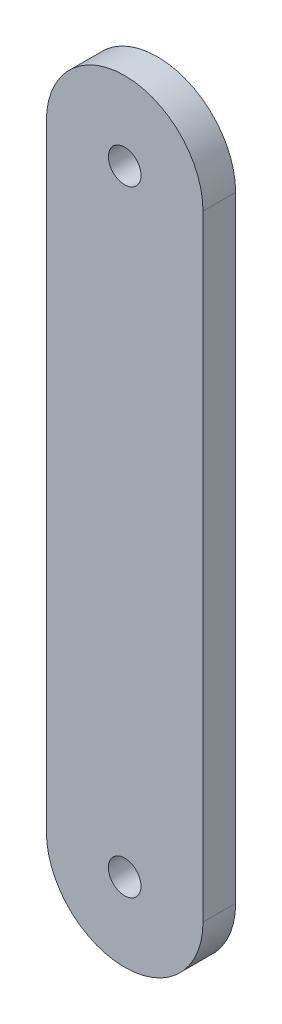
SolidWorks part; units mm, degrees
ref_plane "前视基准面" through (0, 0, 0) normal (0, 0, 1) x (1, 0, 0)
ref_plane "上视基准面" through (0, 0, 0) normal (0, 1, 0) x (1, 0, 0)
ref_plane "右视基准面" through (0, 0, 0) normal (1, 0, 0) x (0, 0, -1)
ref_plane "基准面4" through (0, 0, 5) normal (0, 0, 1) x (1, 0, 0)
sketch "草图1" plane through (0, 0, 5) normal (0, 0, 1) x (1, 0, 0)
  line L0 (12, -47.16) -> (12, 47.16)
  line L1 (-12, 47.16) -> (-12, -47.16)
  circle A0 centre (0, -47.16) radius 2.5
  circle A1 centre (0, 47.16) radius 2.5
  arc A2 (12, 47.16) -> (-12, 47.16) centre (0, 47.16) ccw
  arc A3 (-12, -47.16) -> (12, -47.16) centre (0, -47.16) ccw
  dimension "D1" = 5
  dimension "D2" = 5
  dimension "D3" = 94.32
extrude "凸台-拉伸1" add sketch "草图1" against normal blind 5
